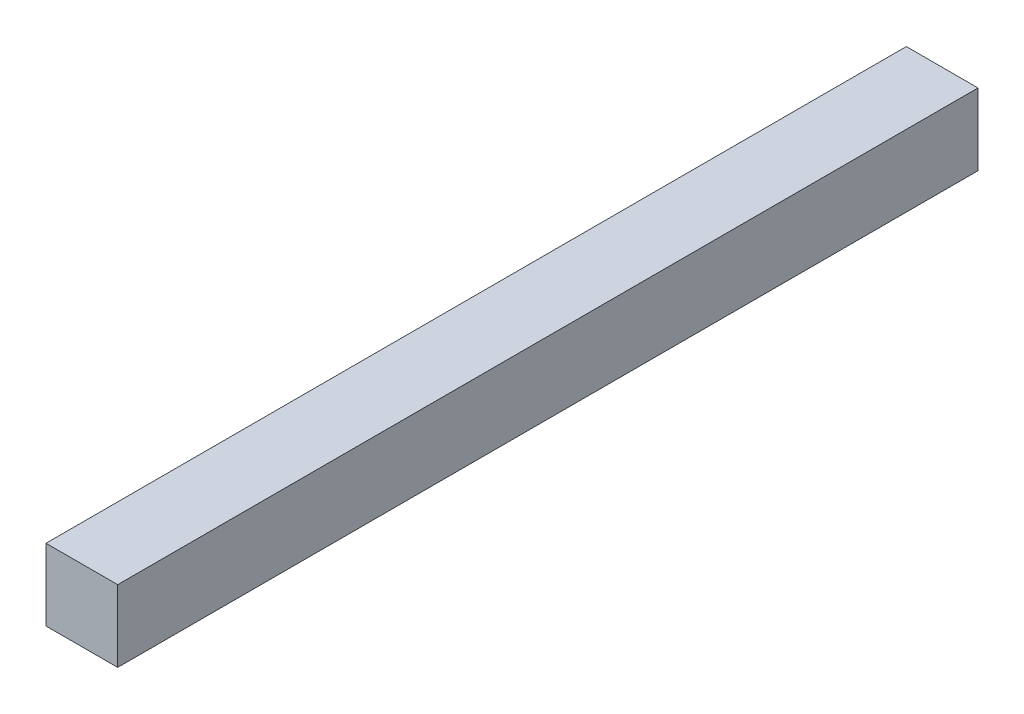
SolidWorks part; units mm, degrees
material "Brass"
ref_plane "Front Plane" through (0, 0, 0) normal (0, 0, 1) x (1, 0, 0)
ref_plane "Top Plane" through (0, 0, 0) normal (0, 1, 0) x (1, 0, 0)
ref_plane "Right Plane" through (0, 0, 0) normal (1, 0, 0) x (0, 0, -1)
sketch "Sketch1" plane through (0, 0, 0) normal (0, 0, 1) x (1, 0, 0)
  line L1 (0, 0) -> (6.35, 0)
  line L2 (0, 0) -> (0, 6.35)
  line L3 (0, 6.35) -> (6.35, 6.35)
  line L4 (6.35, 0) -> (6.35, 6.35)
  dimension "D1" = 6.35
  dimension "D2" = 6.35
extrude "Boss-Extrude1" add sketch "Sketch1" along normal blind 76.2
